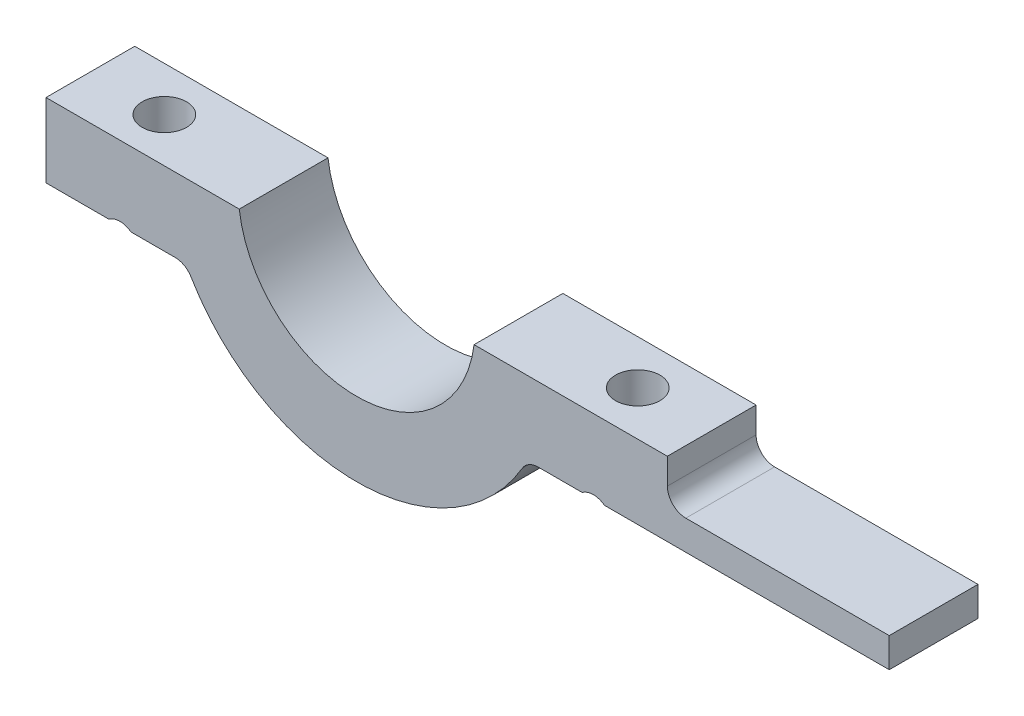
SolidWorks part; units mm, degrees
ref_plane "正面" through (0, 0, 0) normal (0, 0, 1) x (1, 0, 0)
ref_plane "平面" through (0, 0, 0) normal (0, 1, 0) x (1, 0, 0)
ref_plane "右側面" through (0, 0, 0) normal (1, 0, 0) x (0, 0, -1)
sketch "ｽｹｯﾁ1" plane through (0, 0, 0) normal (0, 0, 1) x (1, 0, 0)
  line L0 (-21, -1) -> (-7.9373, -1)
  line L1 (-21, -1) -> (-21, -6)
  line L2 (-21, -6) -> (-16.75, -6)
  line L3 (36, -6) -> (36, -1)
  line L4 (36, -1) -> (7.9373, -1)
  line L5 (-7.9373, -1) -> (7.9373, -1) construction
  line L6 (0, 0) -> (0, -6) construction
  line L7 (-16, -1) -> (-16, -6) construction
  line L8 (16, -1) -> (16, -6) construction
  line L9 (-16, -7) -> (-16, -6) construction
  line L11 (16.75, -6) -> (36, -6)
  line L12 (-15.25, -6) -> (-11.5326, -6)
  line L13 (11.5326, -6) -> (15.25, -6)
  line L15 (10.5239, -7.6321) -> (10.5239, -7.6321)
  line L16 (10.5239, -7.6321) -> (10.5239, -7.6321)
  line L17 (10.5239, -7.6321) -> (10.5239, -7.6321)
  line L19 (-10.5239, -7.6321) -> (-10.5239, -7.6321) construction
  line L20 (-10.5239, -7.6321) -> (-10.5239, -7.6321) construction
  line L21 (-10.5239, -7.6321) -> (-10.5239, -7.6321) construction
  arc A0 (-7.9373, -1) -> (7.9373, -1) centre (0, 0) ccw
  arc A1 (-15.25, -6) -> (-16.75, -6) centre (-16, -7) ccw
  arc A2 (15.25, -6) -> (16.75, -6) centre (16, -7) cw
  arc A4 (-11.5326, -6) -> (11.5326, -6) centre (0, 0) ccw
  arc A5 (10.5239, -7.6321) -> (10.5239, -7.6321) centre (10.5239, -7.6321) cw
  arc A6 (-10.5239, -7.6321) -> (10.5239, -7.6321) centre (0, 0) ccw construction
  arc A7 (-10.5239, -7.6321) -> (-10.5239, -7.6321) centre (-10.5239, -7.6321) ccw construction
  point P34 (0, 0)
  point P35 (0, 0)
  dimension "D1" = 16
  dimension "D5" = 2.5
  dimension "D9" = 5
  dimension "D2" = 5
  dimension "D3" = 1
  dimension "D4" = 16
  dimension "D6" = 1
  dimension "D7" = 5
  dimension "D10" = 20
  dimension "D8" = 5
extrude "ﾎﾞｽ - 押し出し1" add sketch "ｽｹｯﾁ1" along normal mid plane 6 contours L12 A4 L13 A2 L11 L3 L4 A0 L0 L1 L2 A1
sketch "ｽｹｯﾁ3" plane through (0, -6, 0) normal (0, -1, 0) x (1, 0, 0)
  line L0 (-16, 3) -> (-16, -3) construction
  line L1 (-15.25, 3) -> (-16.75, 3) construction
  line L2 (-16.75, -3) -> (-15.25, -3) construction
  line L3 (16, 3) -> (16, -3) construction
  line L4 (16.75, 3) -> (15.25, 3) construction
  line L5 (15.25, -3) -> (16.75, -3) construction
  circle A0 centre (-16, 0) radius 1.5
  circle A1 centre (16, 0) radius 1.5
  dimension "D1" = 3
extrude "ｶｯﾄ - 押し出し1" cut sketch "ｽｹｯﾁ3" against normal through all
sketch "ｽｹｯﾁ4" plane through (0, 0, 3) normal (0, 0, 1) x (1, 0, 0)
  line L1 (36, -1) -> (21, -1)
  line L2 (36, -1) -> (36, -4)
  line L3 (36, -4) -> (21, -4)
  line L4 (21, -1) -> (21, -4)
  dimension "D1" = 15
  dimension "D2" = 3
extrude "ｶｯﾄ - 押し出し2" cut sketch "ｽｹｯﾁ4" against normal through all
fillet "ﾌｨﾚｯﾄ1" radius 1.25 3 edges at (21, -4, 0) (-11.5326, -6, 0) (11.5326, -6, 0)
